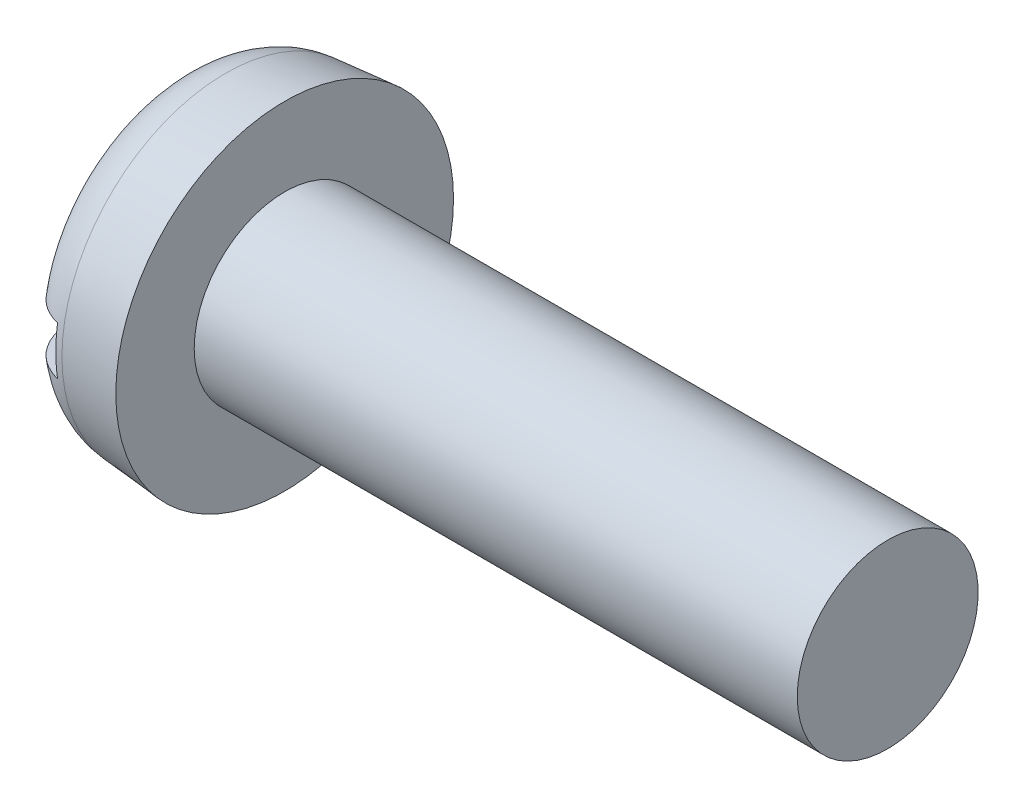
SolidWorks part; units mm, degrees
ref_plane "Plane1" through (0, 0, 0) normal (0, 0, 1) x (1, 0, 0)
ref_plane "Plane2" through (0, 0, 0) normal (0, 1, 0) x (1, 0, 0)
ref_plane "Plane3" through (0, 0, 0) normal (1, 0, 0) x (0, 0, -1)
sketch "BodySke" plane through (0, 0, 0) normal (0, 0, 1) x (1, 0, 0)
  line L0 (1.8, 1.5) -> (1.8, 2.8)
  line L1 (0, 0) -> (0, 2.6425)
  line L2 (-25.4, 0) -> (127, 0) construction
  line L3 (11.8, 0) -> (0, 0)
  line L4 (1.8, 1.5) -> (11.8, 1.5)
  line L5 (11.8, 1.5) -> (11.8, 0)
  line L6 (0, 2.6425) -> (1.8, 2.8)
  line L9 (2.3, 3.0875) -> (2.3, -6.4375) construction
  line L10 (1.8, 6.35) -> (1.8, -3.175) construction
  dimension "Head_ht" = 1.8
  dimension "Diameter" = 3
  dimension "Length" = 10
  dimension "Head_dia" = 5.6
  dimension "Advance" = 0.5
  dimension "Thread_nom" = 10
  dimension "Head_side_angle" = 5
revolve "Base-Revolve" add sketch "BodySke"
cosmetic thread "ThreadCosmetic" [suppressed]
fillet "Fillet1" [suppressed] radius 0.1
fillet "Fillet2" radius 0.9 1 edges at (0, 0, 2.6425)
sketch "Sketch2" plane through (0, 0, 0) normal (1, 0, 0) x (0, 0, -1)
  line L0 (2.8, -0.4) -> (-2.8, -0.4)
  line L1 (2.8, -0.4) -> (2.8, 0.4)
  line L2 (-2.8, 0.4) -> (2.8, 0.4)
  line L3 (-2.8, 0.4) -> (-2.8, -0.4)
  dimension "D1" = 5.6
  dimension "D2" = 2.8
  dimension "Slot_width" = 0.8
  dimension "D3" = 0.4
extrude "Slot" cut sketch "Sketch2" along normal blind 0.7
sketch "ThdSchSke" plane through (0, 0, 0) normal (0, 0, 1) x (1, 0, 0)
  line L0 (2.8, -1.2195) -> (2.6036, -1.5)
  line L1 (2.8, -1.2195) -> (2.9964, -1.5)
  line L2 (2.9964, -1.5) -> (2.9964, -1.875)
  line L3 (-3.175, 0) -> (5.1513, 0) construction
  line L5 (2.9964, -1.875) -> (2.6036, -1.875)
  line L6 (2.6036, -1.875) -> (2.6036, -1.5)
  dimension "Thread_minor" = 2.439
  dimension "Diameter" = 3
  dimension "Start" = 2.8
  dimension "SideAngle" = 55
  dimension "VeeAngle" = 70
  dimension "Overcut" = 3.75
revolve "ThreadSchematic" [suppressed] cut sketch "ThdSchSke" angle 360 about L3
pattern_linear "ThdSchPat" [suppressed]
equation "\"D1@Sketch2\" = \"Head_dia@BodySke\""
equation "\"D2@Sketch2\" = \"D1@Sketch2\" / 2"
equation "\"D3@Sketch2\" = \"Slot_width@Sketch2\" / 2"
equation "\"Thread_length@ThreadCosmetic\" = ((sgn( (\"Length@BodySke\" - \"Advance@BodySke\" * 2.0 ) - \"Thread_nom@BodySke\" )-1)*( (\"Length@BodySke\" - \"Advance@BodySke\"  * 2.0) - \"Thread_nom@BodySke\" ))/-2+ \"Thread_nom@BodySke\""
equation "\"Thread_minor@ThdSchSke\" = \"Thread_minor@ThreadCosmetic\""
equation "\"Diameter@ThdSchSke\" = \"Diameter@BodySke\""
equation "\"Overcut@ThdSchSke\" = \"Diameter@BodySke\" * 1.25"
equation "\"Start@ThdSchSke\" = \"Head_ht@BodySke\" + \"Length@BodySke\" - \"Thread_length@ThreadCosmetic\"  '---Non-countersunk---"
equation "\"Num_threads@ThdSchPat\" = int( \"Thread_length@ThreadCosmetic\" / \"Advance@BodySke\" + 0.999 )  + 1"
equation "\"Advance@ThdSchPat\" = \"Thread_length@ThreadCosmetic\" /  (\"Num_threads@ThdSchPat\" - 1) 'relax it"
